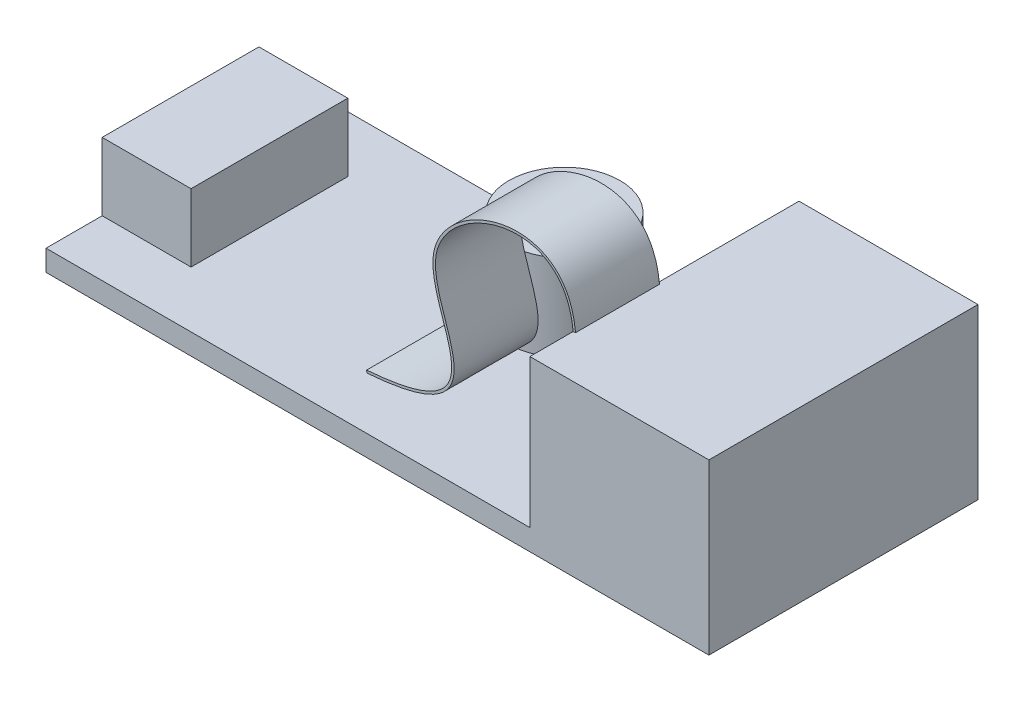
SolidWorks part; units mm, degrees
ref_plane "Front Plane" through (0, 0, 0) normal (0, 0, 1) x (1, 0, 0)
ref_plane "Top Plane" through (0, 0, 0) normal (0, 1, 0) x (1, 0, 0)
ref_plane "Right Plane" through (0, 0, 0) normal (1, 0, 0) x (0, 0, -1)
sketch "Sketch1" plane through (0, 0, 0) normal (0, 1, 0) x (1, 0, 0)
  line L1 (0, 0) -> (53.7, 0)
  line L2 (0, 0) -> (0, 21.8)
  line L3 (0, 21.8) -> (53.7, 21.8)
  line L4 (53.7, 0) -> (53.7, 21.8)
  dimension "D1" = 21.8
  dimension "D2" = 53.7
extrude "Boss-Extrude1" add sketch "Sketch1" along normal blind 1.7
sketch "Sketch2" plane through (0, 1.7, 0) normal (0, 1, 0) x (1, 0, 0)
  line L0 (53.7, 0) -> (53.7, 21.8) construction
  line L1 (53.7, 21.8) -> (39.2, 21.8)
  line L2 (53.7, 21.8) -> (53.7, 0)
  line L3 (53.7, 0) -> (39.2, 0)
  line L4 (39.2, 21.8) -> (39.2, 0)
  line L5 (53.7, 21.8) -> (0, 21.8) construction
  line L6 (0, 0) -> (53.7, 0) construction
  dimension "D1" = 14.5
extrude "Boss-Extrude2" add sketch "Sketch2" along normal blind 12
ref_plane "Plane1" through (0, 0, -3.5) normal (0, 0, 1) x (1, 0, 0)
sketch "Sketch3" plane through (0, 0, -3.5) normal (0, 0, 1) x (1, 0, 0)
  line L0 (39.2, 13.7) -> (39.3991, 13.7189)
  line L1 (22.4909, 2.4396) -> (22.4759, 2.639)
  spline S0 degree 3 poles (39.2, 13.7) (38.4876, 21.2039) (19.6659, 15.1064) (34.7036, 3.3582) (22.4909, 2.4396) knots 0 0 0 0 0.499649 1 1 1 1
  spline S1 degree 1 poles (39.3991, 13.7189) (22.4759, 2.639) knots 0 0 1 1 construction
  spline S2 degree 3 poles (39.3991, 13.7189) (39.3772, 13.95) (39.3129, 14.4227) (39.1212, 15.2576) (38.7629, 16.1688) (38.1682, 17.0369) (37.1899, 17.9105) (35.6995, 18.4872) (33.7199, 18.4782) (31.745, 17.8948) (29.3773, 16.5029) (27.7807, 14.3641) (27.8427, 11.9326) (28.3578, 10.1113) (28.9943, 8.3322) (29.4222, 6.6748) (29.3309, 5.2542) (28.6144, 4.2775) (27.4396, 3.6064) (26.2132, 3.1816) (24.8602, 2.9036) (23.5831, 2.7348) (22.8364, 2.6661) (22.4759, 2.639) knots 0 0 0 0 0.015625 0.03125 0.0625 0.09375 0.125 0.1875 0.25 0.3125 0.375 0.5 0.5625 0.625 0.6875 0.75 0.8125 0.875 0.90625 0.9375 0.96875 0.984375 1 1 1 1
  dimension "D1" = 0.2
extrude "Boss-Extrude3" add sketch "Sketch3" against normal blind 6.8 separate body
sketch "Sketch4" plane through (0, 1.7, 0) normal (0, 1, 0) x (1, 0, 0)
  line L0 (25.5, 21) -> (32.3048, 21) construction
  line L1 (0, 0) -> (39.2, 0) construction
  line L2 (30, 16.5) -> (30, 30.3879) construction
  line L3 (0, 21.8) -> (0, 0) construction
  circle A0 centre (25.5, 16.5) radius 4.5
  dimension "D1" = 9
  dimension "D2" = 21
  dimension "D3" = 30
extrude "Boss-Extrude4" add sketch "Sketch4" along normal blind 7
sketch "Sketch5" plane through (0, 1.7, 0) normal (0, 1, 0) x (1, 0, 0)
  line L0 (0, 21.8) -> (0, 0) construction
  line L1 (0, 17.25) -> (7.2, 17.25)
  line L2 (0, 17.25) -> (0, 4.55)
  line L3 (0, 4.55) -> (7.2, 4.55)
  line L4 (7.2, 17.25) -> (7.2, 4.55)
  line L5 (7.2, 10.9) -> (53.7, 10.9) construction
  line L6 (53.7, 0) -> (53.7, 21.8) construction
  dimension "D1" = 12.7
  dimension "D2" = 7.2
extrude "Boss-Extrude5" add sketch "Sketch5" along normal blind 5.5
sketch "Sketch6" plane through (0, 0, 0) normal (0, -1, 0) x (1, 0, 0)
  line L0 (0, -21.8) -> (0, 0) construction
  line L1 (0, -6.9) -> (6, -6.9)
  line L2 (0, -6.9) -> (0, -14.9)
  line L3 (0, -14.9) -> (6, -14.9)
  line L4 (6, -6.9) -> (6, -14.9)
  line L5 (6, -10.9) -> (53.7, -10.9) construction
  line L6 (53.7, 0) -> (53.7, -21.8) construction
  dimension "D1" = 8
  dimension "D2" = 6
extrude "Boss-Extrude6" add sketch "Sketch6" along normal blind 3.5
